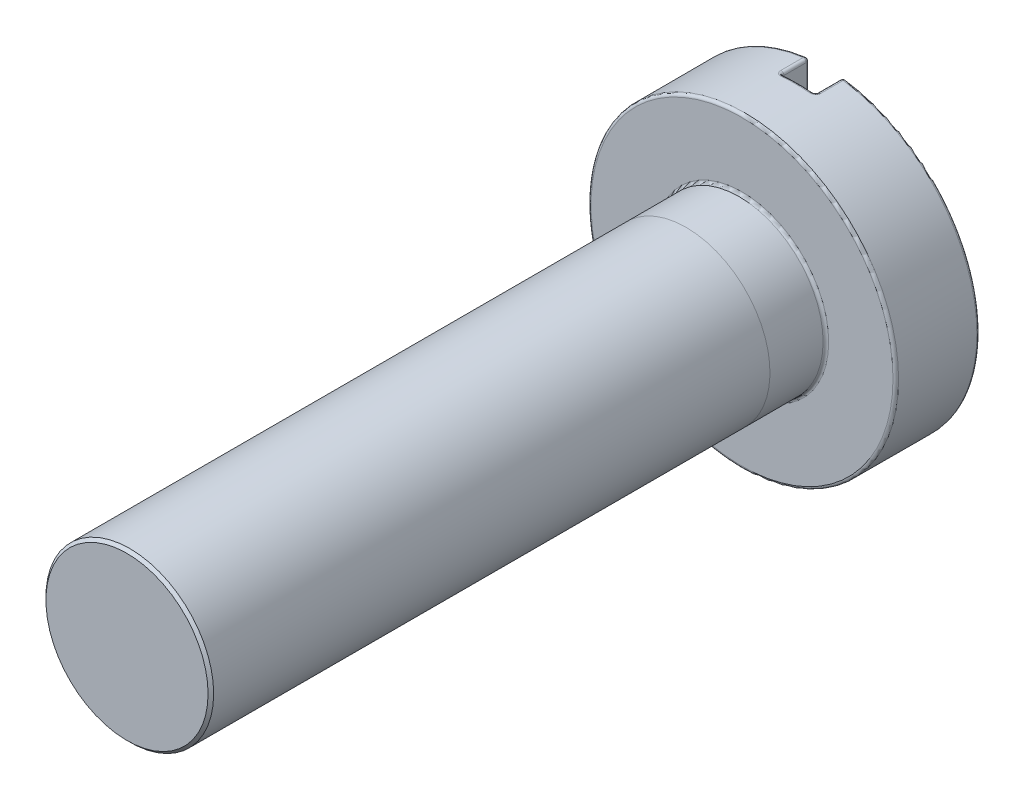
SolidWorks part; units mm, degrees
ref_plane "Front Plane" through (0, 0, 0) normal (0, 0, 1) x (1, 0, 0)
ref_plane "Top Plane" through (0, 0, 0) normal (0, 1, 0) x (1, 0, 0)
ref_plane "Right Plane" through (0, 0, 0) normal (1, 0, 0) x (0, 0, -1)
sketch "Sketch1" plane through (0, 0, 0) normal (0, 0, 1) x (1, 0, 0)
  circle A0 centre (0, 0) radius 1.5
  dimension "D1" = 3
extrude "Boss-Extrude1" add sketch "Sketch1" along normal blind 11
sketch "Sketch2" plane through (0, 0, 0) normal (0, 0, 1) x (1, 0, 0)
  circle A2 centre (0, 0) radius 2.75
  circle A3 centre (0, 0) radius 2.75
  dimension "D1" = 1.25
extrude "Boss-Extrude2" add sketch "Sketch2" against normal blind 1.5
sketch "Sketch3" plane through (0, 0, -1.5) normal (0, 0, -1) x (-1, 0, 0)
  line L1 (-0.3, 4.1969) -> (0.3, 4.1969)
  line L2 (-0.3, 4.1969) -> (-0.3, -4.1969)
  line L3 (-0.3, -4.1969) -> (0.3, -4.1969)
  line L4 (0.3, 4.1969) -> (0.3, -4.1969)
  line L5 (-0.3, 4.1969) -> (0.3, -4.1969) construction
  line L6 (-0.3, -4.1969) -> (0.3, 4.1969) construction
  point P0 (0, 0)
  dimension "D1" = 0.6
extrude "Cut-Extrude1" cut sketch "Sketch3" against normal blind 0.5
fillet "Fillet1" radius 0.05 13 edges at (0.3, 2.7336, -1.25) (0.3, -2.7336, -1.25) (-0.3, -2.7336, -1.25) (-0.3, 2.7336, -1.25) (0, -2.75, -1) (0, 2.75, -1) (0.3, 0, -1) (-0.3, 0, -1) (0.3, 0, -1.5) (2.75, 0, -1.5) (-0.3, 0, -1.5) (-2.75, 0, -1.5) (1.5, 0, 0)
fillet "Fillet2" radius 0.05 1 edges at (2.75, 0, 0)
chamfer "Chamfer1" distance 0.05 angle 45 1 edges at (1.5, 0, 11)
sketch "Sketch4" plane through (0, 0, 0) normal (1, 0, 0) x (0, 0, -1)
  line L0 (-1, 3.701) -> (-1, -3.2348)
  line L1 (-11, 1.45) -> (-11, -1.45) construction
  dimension "D1" = 10
split line "Split Line1"
